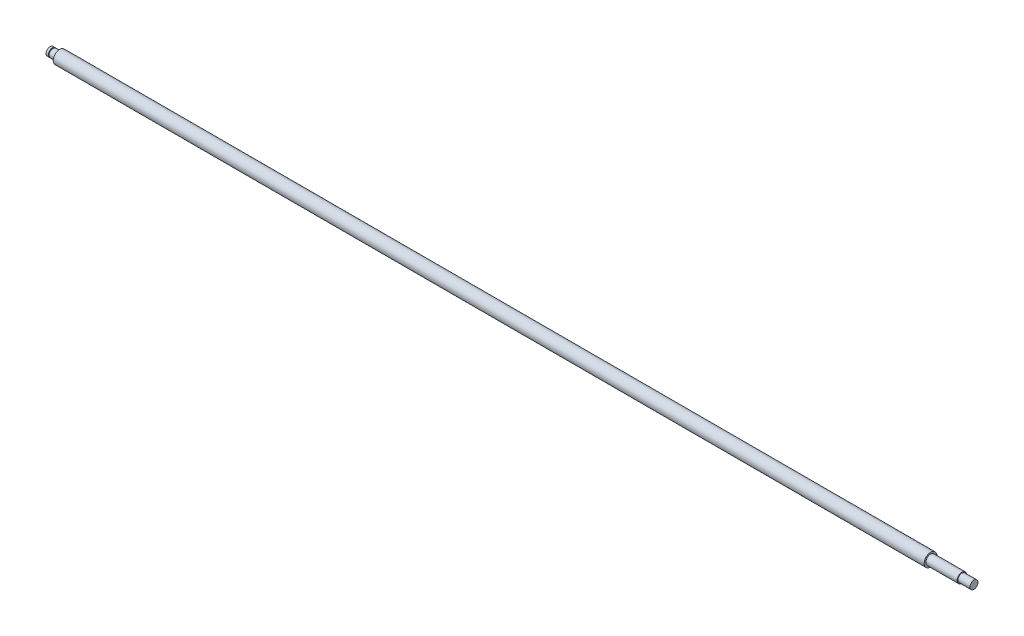
SolidWorks part; units mm, degrees
ref_plane "Plan de face" through (0, 0, 0) normal (0, 0, 1) x (1, 0, 0)
ref_plane "Plan de dessus" through (0, 0, 0) normal (0, 1, 0) x (1, 0, 0)
ref_plane "Plan de droite" through (0, 0, 0) normal (1, 0, 0) x (0, 0, -1)
sketch "Esquisse1" plane through (0, 0, 0) normal (0, 0, 1) x (1, 0, 0)
  line L0 (-89.4006, 0) -> (1216.033, 0) construction
  line L1 (-88.2233, 0) -> (-88.2233, 5)
  line L2 (-88.2233, 5) -> (-85.3699, 5)
  line L3 (-85.3699, 5) -> (-85.3699, 4)
  line L4 (-85.3699, 4) -> (-84.2199, 4)
  line L5 (-84.2199, 4) -> (-84.2199, 5)
  line L6 (-84.2199, 5) -> (-76.2199, 5)
  line L7 (-76.2199, 5) -> (-76.2199, 8)
  line L8 (-76.2199, 8) -> (1007.7801, 8)
  line L9 (1007.7801, 8) -> (1007.7801, 6)
  line L10 (1007.7801, 6) -> (1034.7801, 6)
  line L11 (1034.7801, 6) -> (1046.7801, 6)
  line L12 (1046.7801, 6) -> (1046.7801, 5)
  line L13 (1046.7801, 5) -> (1061.7801, 5)
  line L14 (1061.7801, 5) -> (1061.7801, 0)
  line L15 (-88.2233, 0) -> (1061.7801, 0)
  dimension "D1" = 5
  dimension "D2" = 2.8534
  dimension "D3" = 1
  dimension "D4" = 1.15
  dimension "D5" = 8
  dimension "D6" = 3
  dimension "D7" = 1
  dimension "D8" = 1084
  dimension "D9" = 2
  dimension "D10" = 27
  dimension "D11" = 12
  dimension "D12" = 1
  dimension "D13" = 15
  dimension "D14" = 5
revolve "Révolution1" add sketch "Esquisse1" angle 360 about L0
